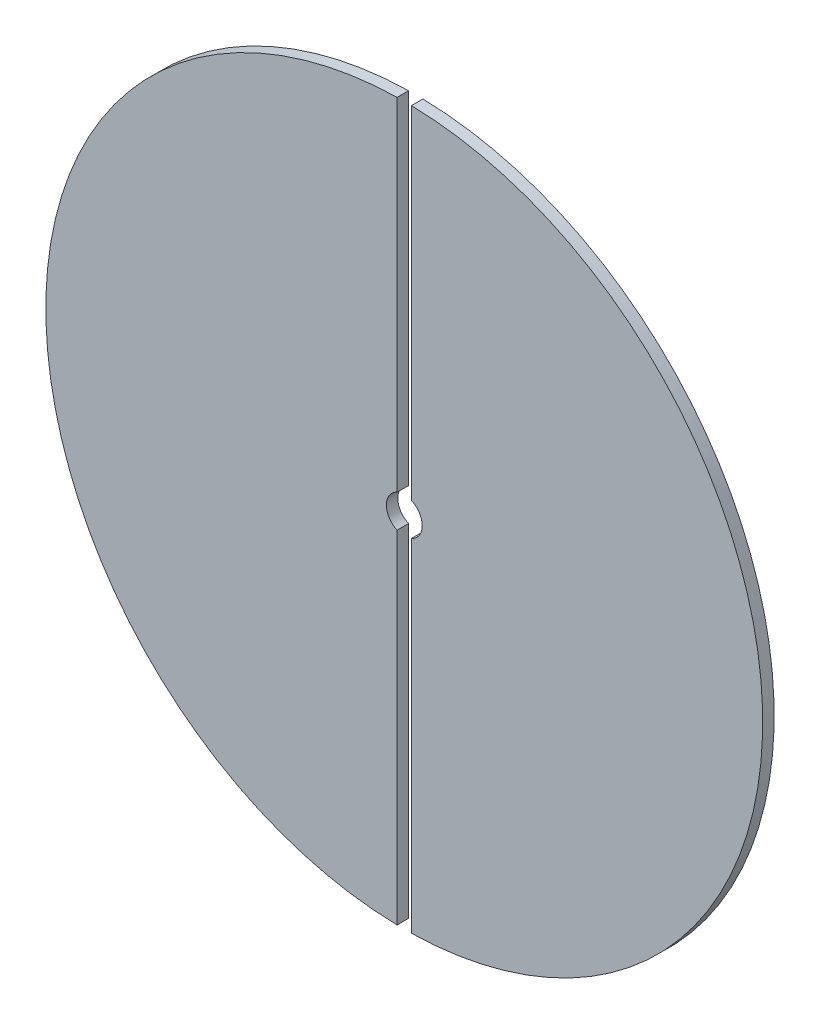
SolidWorks part; units mm, degrees
ref_plane "Ebene vorne" through (0, 0, 0) normal (0, 0, 1) x (1, 0, 0)
ref_plane "Ebene oben" through (0, 0, 0) normal (0, 1, 0) x (1, 0, 0)
ref_plane "Ebene rechts" through (0, 0, 0) normal (1, 0, 0) x (0, 0, -1)
sketch "Skizze1" plane through (0, 0, 0) normal (0, 0, 1) x (1, 0, 0)
  line L0 (0, -50) -> (0, 50) construction
  line L1 (-1, 49.99) -> (-1, 2.2913)
  line L2 (1, 49.99) -> (1, 2.2913)
  line L3 (-1, 2.2913) -> (-1, -2.2913) construction
  line L4 (-1, -2.2913) -> (-1, -49.99)
  line L5 (1, 2.2913) -> (1, -2.2913) construction
  line L6 (1, -2.2913) -> (1, -49.99)
  arc A0 (-1, 49.99) -> (-1, -49.99) centre (0, 0) ccw
  arc A1 (0, 50) -> (-1, 49.99) centre (0, 0) ccw construction
  arc A2 (1, 49.99) -> (0, 50) centre (0, 0) ccw construction
  arc A3 (-1, -49.99) -> (0, -50) centre (0, 0) ccw construction
  arc A4 (1, -49.99) -> (1, 49.99) centre (0, 0) ccw
  arc A5 (0, -50) -> (1, -49.99) centre (0, 0) ccw construction
  arc A6 (-1, 2.2913) -> (-1, -2.2913) centre (0, 0) ccw
  arc A7 (0, 2.5) -> (-1, 2.2913) centre (0, 0) ccw construction
  arc A8 (1, 2.2913) -> (0, 2.5) centre (0, 0) ccw construction
  arc A9 (0, -2.5) -> (1, -2.2913) centre (0, 0) ccw construction
  arc A10 (1, -2.2913) -> (1, 2.2913) centre (0, 0) ccw
  arc A11 (-1, -2.2913) -> (0, -2.5) centre (0, 0) ccw construction
  point P6 (0, 0)
  dimension "D1" = 100
  dimension "D3" = 5
  dimension "D2" = 2
extrude "Aufsatz-Linear austragen1" add sketch "Skizze1" along normal blind 1.6
